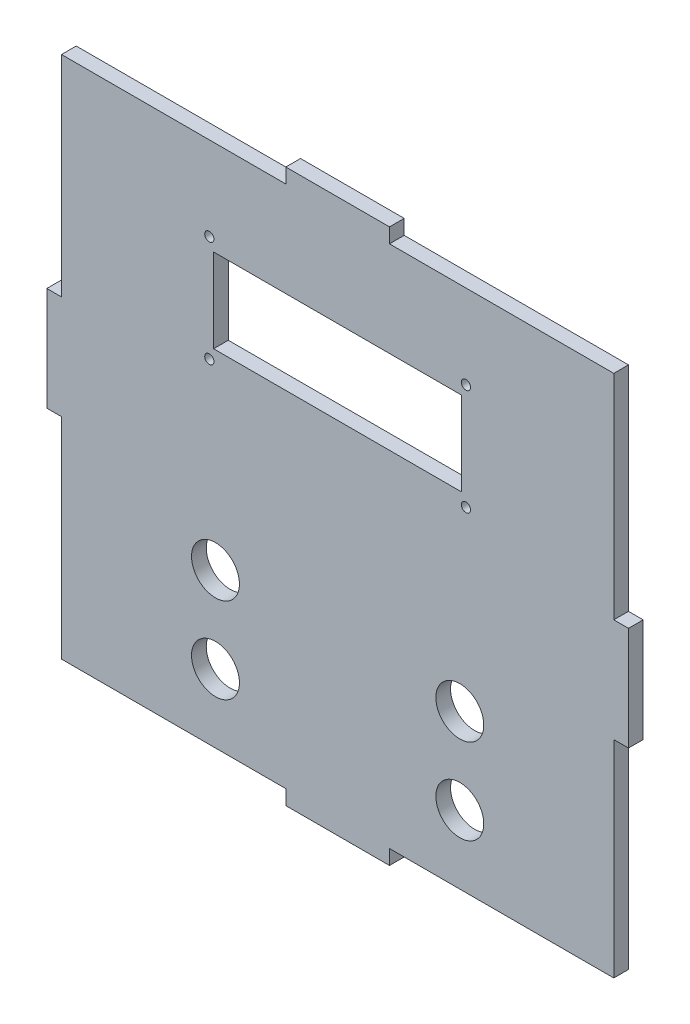
SolidWorks part; units mm, degrees
ref_plane "Front Plane" through (0, 0, 0) normal (0, 0, 1) x (1, 0, 0)
ref_plane "Top Plane" through (0, 0, 0) normal (0, 1, 0) x (1, 0, 0)
ref_plane "Right Plane" through (0, 0, 0) normal (1, 0, 0) x (0, 0, -1)
sketch "Sketch1" plane through (0, 0, 0) normal (0, 0, 1) x (1, 0, 0)
  line L0 (15.15, 76.515) -> (80.7, 76.515)
  line L1 (-80.7, -76.515) -> (-15.15, -76.515)
  line L2 (-80.7, -76.515) -> (-80.7, -15.15)
  line L3 (-80.7, 76.515) -> (-15.15, 76.515)
  line L4 (80.7, -76.515) -> (80.7, -16.165)
  line L5 (-80.7, -76.515) -> (80.7, 76.515) construction
  line L6 (-80.7, 76.515) -> (80.7, -76.515) construction
  line L8 (-15.15, 76.515) -> (-15.15, 80.815)
  line L9 (-15.15, 80.815) -> (15.15, 80.815)
  line L10 (15.15, 76.515) -> (15.15, 80.815)
  line L12 (15.15, -76.515) -> (15.15, -80.815)
  line L13 (15.15, -80.815) -> (-15.15, -80.815)
  line L14 (-15.15, -76.515) -> (-15.15, -80.815)
  line L15 (-80.7, 15.15) -> (-85, 15.15)
  line L17 (-80.7, -15.15) -> (-85, -15.15)
  line L18 (-85, 15.15) -> (-85, -15.15)
  line L19 (80.7, 14.135) -> (85, 14.135)
  line L21 (80.7, -16.165) -> (85, -16.165)
  line L22 (85, 14.135) -> (85, -16.165)
  line L23 (-80.7, 15.15) -> (-80.7, 76.515)
  line L24 (80.7, 14.135) -> (80.7, 76.515)
  line L25 (15.15, -76.515) -> (80.7, -76.515)
  line L27 (-37.5, 52.015) -> (37.5, 52.015) construction
  line L28 (-37.5, 52.015) -> (-37.5, 21.015) construction
  line L29 (-37.5, 21.015) -> (37.5, 21.015) construction
  line L30 (37.5, 52.015) -> (37.5, 21.015) construction
  line L31 (-37.5, 52.015) -> (37.5, 21.015) construction
  line L32 (-37.5, 21.015) -> (37.5, 52.015) construction
  line L33 (-36.25, 48.765) -> (36.25, 48.765)
  line L34 (-36.25, 48.765) -> (-36.25, 24.265)
  line L35 (-36.25, 24.265) -> (36.25, 24.265)
  line L36 (36.25, 48.765) -> (36.25, 24.265)
  line L37 (-36.25, 48.765) -> (36.25, 24.265) construction
  line L38 (-36.25, 24.265) -> (36.25, 48.765) construction
  circle A0 centre (35.7, -31.515) radius 7
  circle A1 centre (35.7, -56.515) radius 7
  circle A2 centre (-35.7, -56.515) radius 7
  circle A3 centre (-35.7, -31.515) radius 7
  circle A4 centre (-37.5, 52.015) radius 1.35
  circle A5 centre (-37.5, 21.015) radius 1.35
  circle A6 centre (37.5, 21.015) radius 1.35
  circle A7 centre (37.5, 52.015) radius 1.35
  point P0 (0, 0)
  point P22 (0, -80.815)
  point P23 (0, 80.815)
  point P26 (0, 36.515)
  point P31 (0, 36.515)
  dimension "D14" = 2.7
  dimension "D15" = 14
  dimension "D1" = 153.03
  dimension "D2" = 161.4
  dimension "D3" = 30.3
  dimension "D4" = 4.3
  dimension "D5" = 40
  dimension "D6" = 75
  dimension "D7" = 31
  dimension "D8" = 24.5
  dimension "D9" = 72.5
  dimension "D16" = 45
  dimension "D17" = 45
  dimension "D18" = 20
  dimension "D19" = 25
  dimension "D20" = 62.38
extrude "Boss-Extrude1" add sketch "Sketch1" along normal blind 4.3
